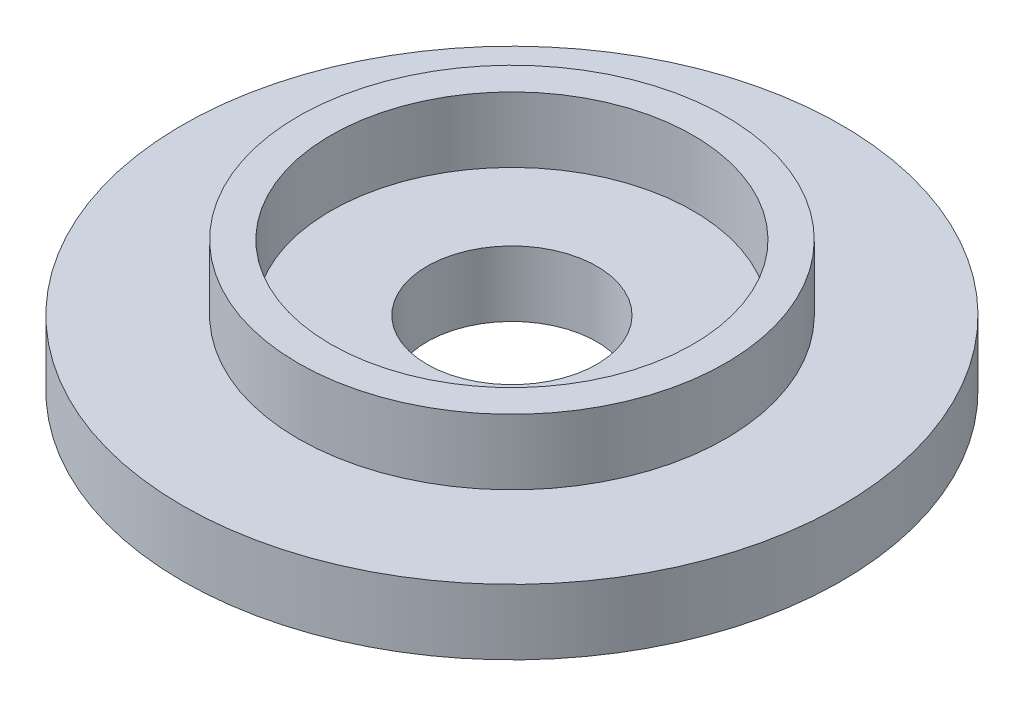
SolidWorks part; units mm, degrees
ref_plane "Front Plane" through (0, 0, 0) normal (0, 0, 1) x (1, 0, 0)
ref_plane "Top Plane" through (0, 0, 0) normal (0, 1, 0) x (1, 0, 0)
ref_plane "Right Plane" through (0, 0, 0) normal (1, 0, 0) x (0, 0, -1)
sketch "Sketch2" plane through (0, 0, 0) normal (0, 1, 0) x (1, 0, 0)
  circle A0 centre (0, 0) radius 64
  dimension "D1" = 128
extrude "Boss-Extrude1" add sketch "Sketch2" along normal blind 12.7
sketch "Sketch3" plane through (0, 12.7, 0) normal (0, 1, 0) x (1, 0, 0)
  circle A0 centre (0, 0) radius 41.5157
  circle A1 centre (0, 0) radius 35.1657
  dimension "D1" = 83.0314
  dimension "D2" = 6.35
extrude "Boss-Extrude2" add sketch "Sketch3" along normal blind 12.7
sketch "Sketch4" plane through (0, 25.4, 0) normal (0, 1, 0) x (1, 0, 0)
  circle A0 centre (0, 0) radius 16.4981
  dimension "D1" = 32.9963
extrude "Cut-Extrude1" cut sketch "Sketch4" against normal blind 635
sketch "Sketch6" plane through (0, 12.7, 0) normal (0, 1, 0) x (1, 0, 0)
  line L0 (0, 0) -> (0, 25.4)
  circle A0 centre (0, 38.9) radius 13.5
  point P2 (-145.3241, 38.5249)
  dimension "D1" = 27
